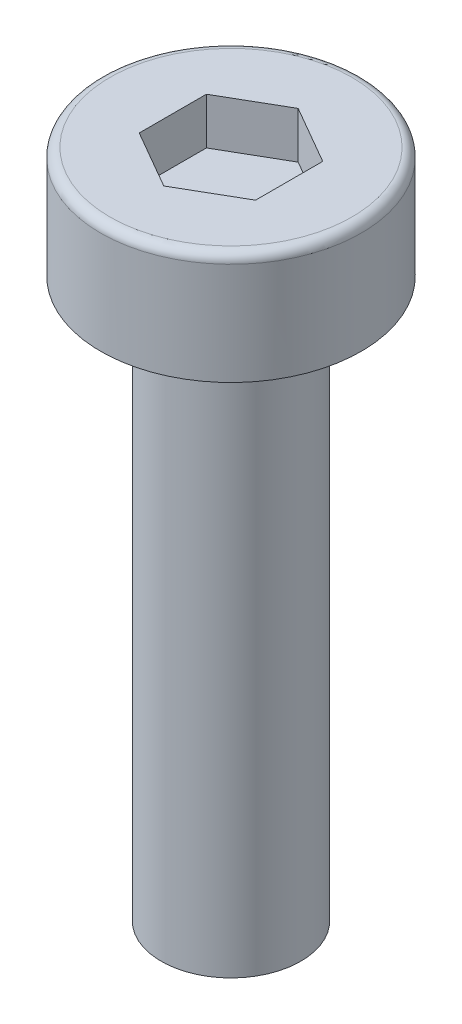
SolidWorks part; units mm, degrees
material "Plain Carbon Steel"
ref_plane "Front Plane" through (0, 0, 0) normal (0, 0, 1) x (1, 0, 0)
ref_plane "Top Plane" through (0, 0, 0) normal (0, 1, 0) x (1, 0, 0)
ref_plane "Right Plane" through (0, 0, 0) normal (1, 0, 0) x (0, 0, -1)
sketch "Sketch1" plane through (0, 0, 0) normal (0, 0, 1) x (1, 0, 0)
  line L0 (0, 0) -> (0, 14.4)
  line L1 (0, 14.4) -> (2.8, 14.4)
  line L2 (2.8, 14.4) -> (2.8, 12)
  line L3 (2.8, 12) -> (1.5, 12)
  line L4 (1.5, 12) -> (1.5, 0)
  line L5 (1.5, 0) -> (0, 0)
  dimension "D1" = 1.5
  dimension "D2" = 12
  dimension "D3" = 2.8
  dimension "D4" = 2.4
revolve "Revolve1" add sketch "Sketch1" angle 360 about L0
sketch "Sketch2" plane through (0, 14.4, 0) normal (0, 1, 0) x (1, 0, 0)
  line L1 (0, -1.4434) -> (1.25, -0.7217)
  line L2 (1.25, -0.7217) -> (1.25, 0.7217)
  line L3 (1.25, 0.7217) -> (0, 1.4434)
  line L4 (0, 1.4434) -> (-1.25, 0.7217)
  line L5 (-1.25, 0.7217) -> (-1.25, -0.7217)
  line L6 (-1.25, -0.7217) -> (0, -1.4434)
  circle A0 centre (0, 0) radius 1.25 construction
  dimension "D1" = 2.5
extrude "Cut-Extrude1" cut sketch "Sketch2" against normal blind 1
fillet "Fillet1" radius 0.2 1 edges at (0, 14.4, -2.8)
